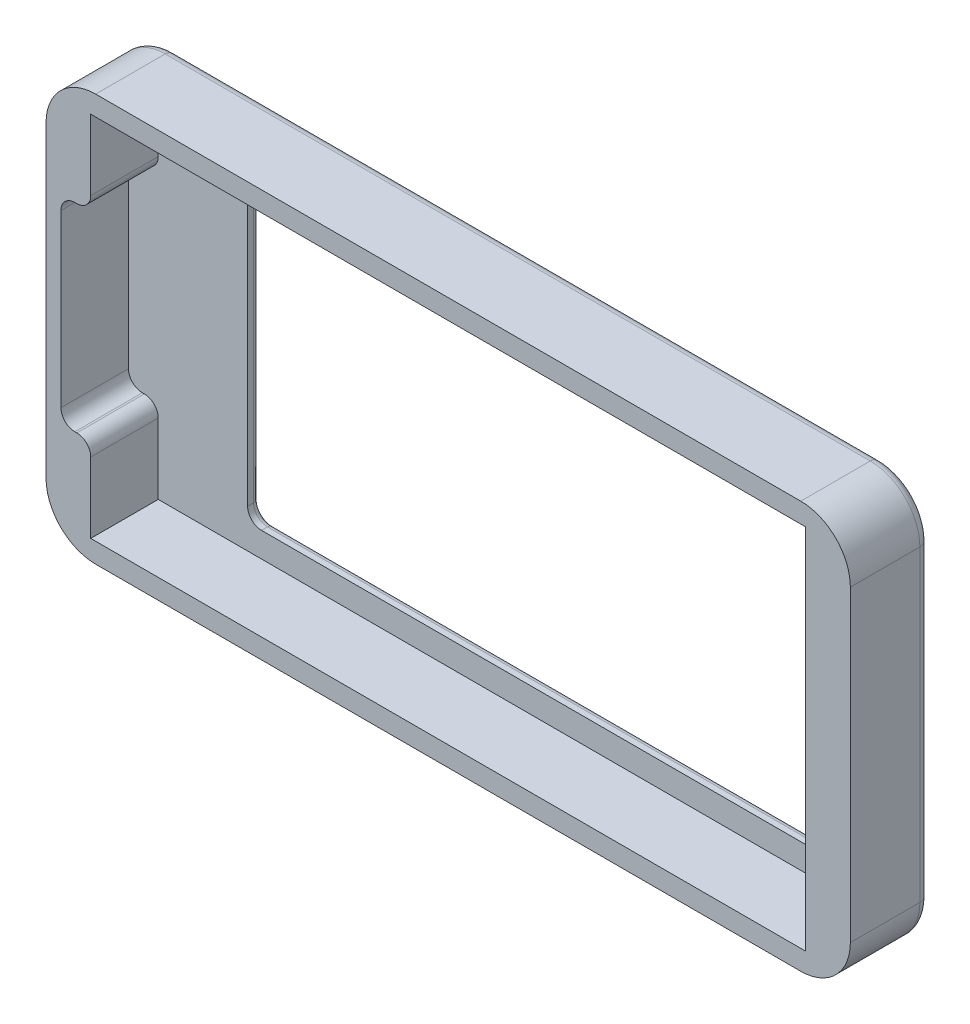
SolidWorks part; units mm, degrees
ref_plane "Front Plane" through (0, 0, 0) normal (0, 0, 1) x (1, 0, 0)
ref_plane "Top Plane" through (0, 0, 0) normal (0, 1, 0) x (1, 0, 0)
ref_plane "Right Plane" through (0, 0, 0) normal (1, 0, 0) x (0, 0, -1)
sketch "Sketch1" plane through (0, 0, 0) normal (0, 0, 1) x (1, 0, 0)
  line L1 (0, 0) -> (81, 0)
  line L2 (0, 0) -> (0, 41)
  line L3 (0, 41) -> (81, 41)
  line L4 (81, 0) -> (81, 41)
  dimension "D1" = 81
  dimension "D2" = 41
extrude "Boss-Extrude1" add sketch "Sketch1" along normal blind 8
sketch "Sketch2" plane through (0, 0, 8) normal (0, 0, 1) x (1, 0, 0)
  line L0 (0, 41) -> (0, 0) construction
  line L1 (4.5, 39) -> (76.5, 39)
  line L2 (4.5, 39) -> (4.5, 2)
  line L3 (4.5, 2) -> (76.5, 2)
  line L4 (76.5, 39) -> (76.5, 2)
  line L5 (81, 0) -> (81, 41) construction
  line L6 (81, 41) -> (0, 41) construction
  line L7 (0, 0) -> (81, 0) construction
  dimension "D1" = 4.5
  dimension "D2" = 4.5
  dimension "D3" = 2
  dimension "D4" = 2
extrude "Cut-Extrude1" cut sketch "Sketch2" against normal blind 6.8
sketch "Sketch3" plane through (0, 0, 8) normal (0, 0, 1) x (1, 0, 0)
  line L0 (4.5, 39) -> (4.5, 2) construction
  line L1 (4.5, 30.5) -> (1.5, 30.5)
  line L2 (4.5, 30.5) -> (4.5, 10.5)
  line L3 (4.5, 10.5) -> (1.5, 10.5)
  line L4 (1.5, 30.5) -> (1.5, 10.5)
  line L6 (76.5, 39) -> (4.5, 39) construction
  dimension "D1" = 20
  dimension "D2" = 8.5
  dimension "D3" = 3
extrude "Cut-Extrude2" cut sketch "Sketch3" against normal blind 6.8
sketch "Sketch4" plane through (0, 0, 1.2) normal (0, 0, 1) x (1, 0, 0)
  line L0 (4.5, 39) -> (4.5, 30.5) construction
  line L1 (13.5, 36.5) -> (74.1, 36.5)
  line L2 (13.5, 36.5) -> (13.5, 4.5)
  line L3 (13.5, 4.5) -> (74.1, 4.5)
  line L4 (74.1, 36.5) -> (74.1, 4.5)
  line L5 (76.5, 2) -> (76.5, 39) construction
  line L6 (76.5, 39) -> (4.5, 39) construction
  line L7 (4.5, 2) -> (76.5, 2) construction
  dimension "D1" = 9
  dimension "D2" = 2.4
  dimension "D3" = 2.5
  dimension "D4" = 2.5
extrude "Cut-Extrude3" cut sketch "Sketch4" against normal blind 6.4
fillet "Fillet1" radius 1.4 8 edges at (4.5, 10.5, 4.6) (1.5, 10.5, 4.6) (1.5, 30.5, 4.6) (4.5, 30.5, 4.6) (74.1, 4.5, 0.6) (13.5, 4.5, 0.6) (13.5, 36.5, 0.6) (74.1, 36.5, 0.6)
fillet "Fillet2" radius 5 4 edges at (0, 0, 4) (81, 0, 4) (81, 41, 4) (0, 41, 4)
fillet "Fillet3" radius 0.6 8 edges at (13.9101, 36.0899, 0) (13.5, 20.5, 0) (13.9101, 4.9101, 0) (43.8, 4.5, 0) (73.6899, 4.9101, 0) (74.1, 20.5, 0) (73.6899, 36.0899, 0) (43.8, 36.5, 0)
fillet "Fillet4" radius 1 8 edges at (79.5355, 39.5355, 0) (81, 20.5, 0) (79.5355, 1.4645, 0) (40.5, 0, 0) (1.4645, 1.4645, 0) (0, 20.5, 0) (1.4645, 39.5355, 0) (40.5, 41, 0)
